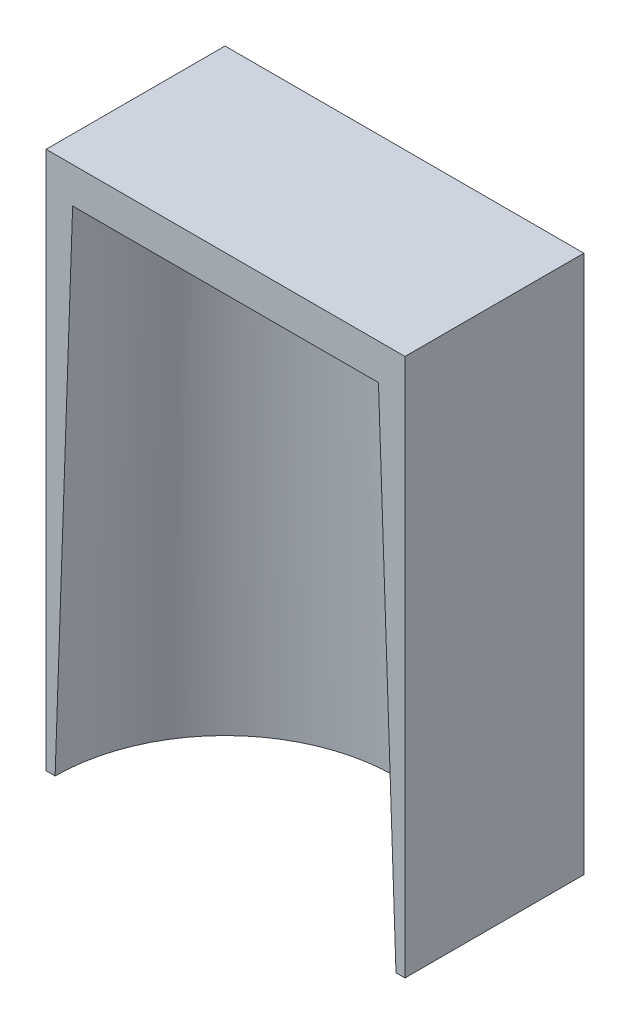
SolidWorks part; units mm, degrees
ref_plane "Front Plane" through (0, 0, 0) normal (0, 0, 1) x (1, 0, 0)
ref_plane "Top Plane" through (0, 0, 0) normal (0, 1, 0) x (1, 0, 0)
ref_plane "Right Plane" through (0, 0, 0) normal (1, 0, 0) x (0, 0, -1)
sketch "Sketch1" plane through (0, 0, 0) normal (0, 1, 0) x (1, 0, 0)
  line L1 (-50, 50) -> (50, 50)
  line L2 (-50, 50) -> (-50, 0.1478)
  line L3 (-50, 0.1478) -> (50, 0.1478)
  line L4 (50, 50) -> (50, 0.1478)
  point P0 (0, 0)
  dimension "D2" = 100
extrude "Boss-Extrude3" add sketch "Sketch1" along normal blind 150
sketch "Sketch2" plane through (0, 0, 0) normal (0, -1, 0) x (1, 0, 0)
  circle A0 centre (0, 0) radius 47.5
  dimension "D1" = 95
extrude "Cut-Extrude1" cut sketch "Sketch2" against normal blind 140 draft 2
